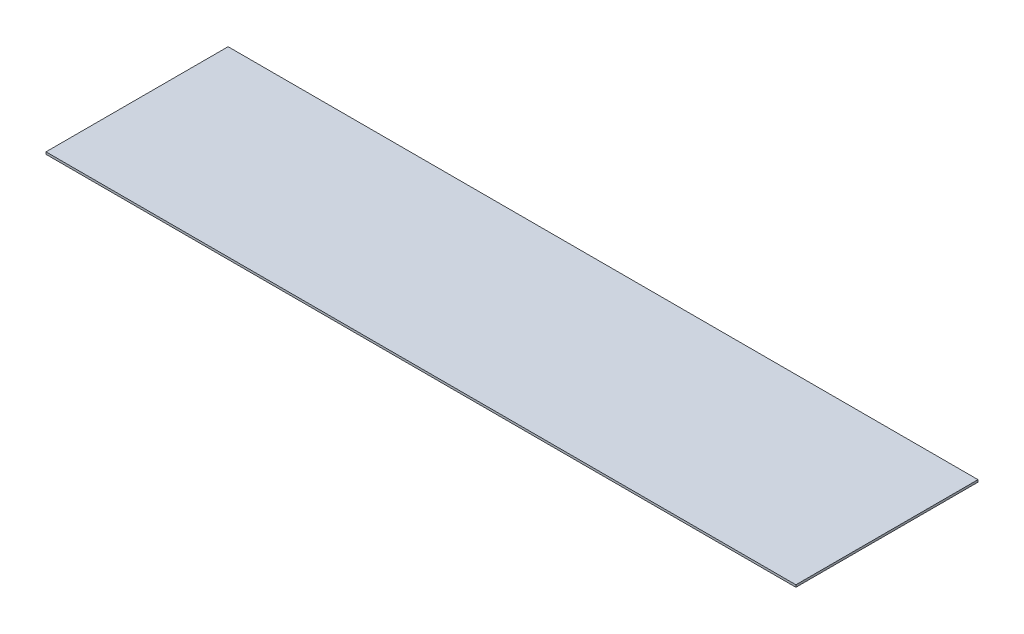
SolidWorks part; units mm, degrees
ref_plane "Front Plane" through (0, 0, 0) normal (0, 0, 1) x (1, 0, 0)
ref_plane "Top Plane" through (0, 0, 0) normal (0, 1, 0) x (1, 0, 0)
ref_plane "Right Plane" through (0, 0, 0) normal (1, 0, 0) x (0, 0, -1)
sketch "Sketch1" plane through (0, 0, 0) normal (0, 1, 0) x (1, 0, 0)
  line L1 (0, 0) -> (863.6, 0)
  line L2 (0, 0) -> (0, 209.7)
  line L3 (0, 209.7) -> (863.6, 209.7)
  line L4 (863.6, 0) -> (863.6, 209.7)
  dimension "D1" = 863.6
  dimension "D2" = 209.7
extrude "Boss-Extrude1" add sketch "Sketch1" along normal blind 2.54
